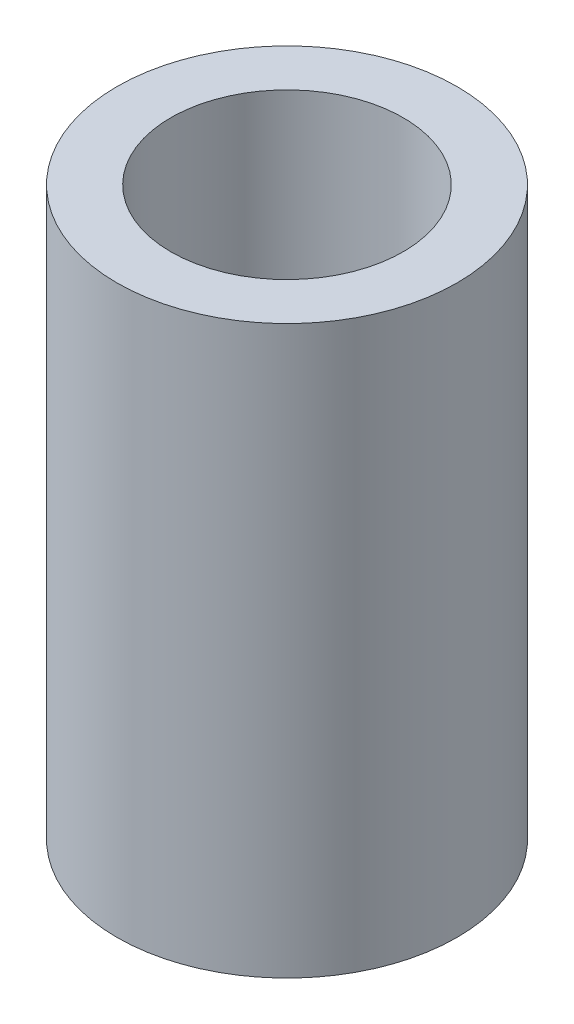
SolidWorks part; units mm, degrees
ref_plane "Front Plane" through (0, 0, 0) normal (0, 0, 1) x (1, 0, 0)
ref_plane "Top Plane" through (0, 0, 0) normal (0, 1, 0) x (1, 0, 0)
ref_plane "Right Plane" through (0, 0, 0) normal (1, 0, 0) x (0, 0, -1)
sketch "草圖1" plane through (0, 0, 0) normal (0, 1, 0) x (1, 0, 0)
  circle A0 centre (0, 0) radius 2.05
  circle A1 centre (0, 0) radius 3
  dimension "D1" = 6
  dimension "D2" = 4.1
extrude "填料-伸長1" add sketch "草圖1" along normal blind 10
